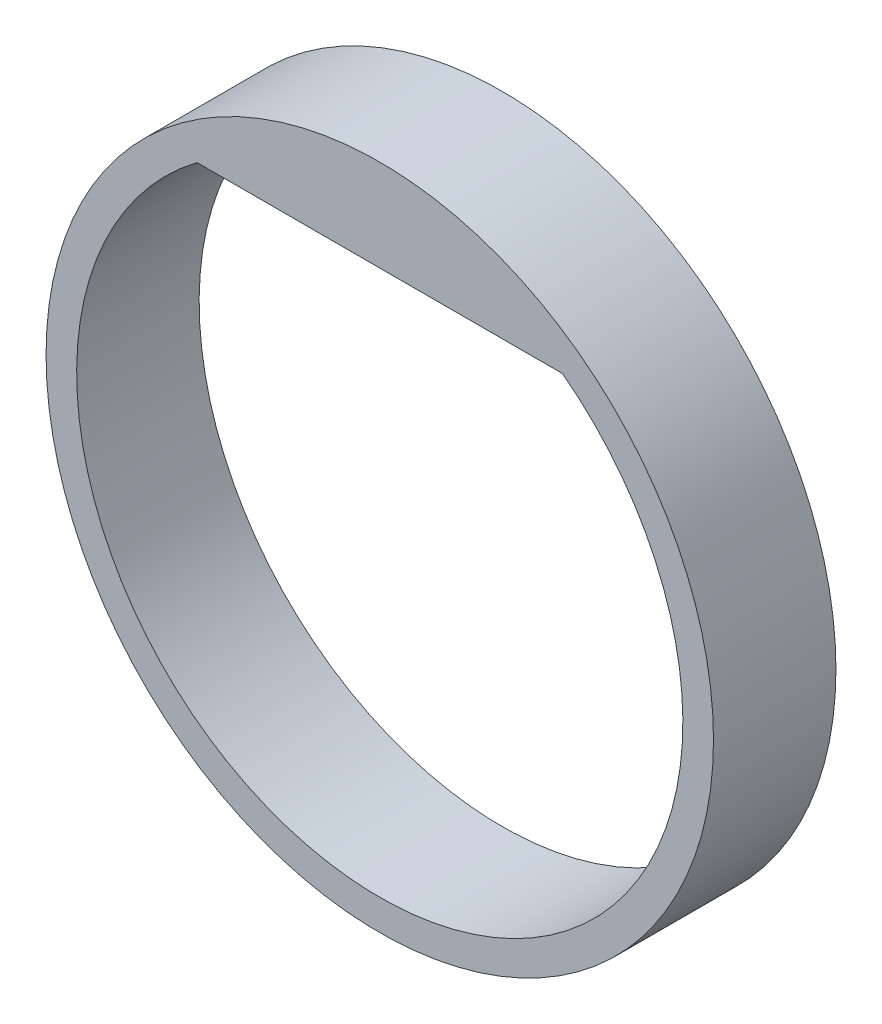
SolidWorks part; units mm, degrees
ref_plane "Vorne" through (0, 0, 0) normal (0, 0, 1) x (1, 0, 0)
ref_plane "Oben" through (0, 0, 0) normal (0, 1, 0) x (1, 0, 0)
ref_plane "Seite" through (0, 0, 0) normal (1, 0, 0) x (0, 0, -1)
sketch "Skizze1" plane through (0, 0, 0) normal (0, 0, 1) x (1, 0, 0)
  line L0 (2.9833, 3.95) -> (-2.9833, 3.95)
  circle A1 centre (0, 0) radius 5.45
  arc A2 (-2.9833, 3.95) -> (2.9833, 3.95) centre (0, 0) ccw
  dimension "D1" = 3.95
  dimension "D2" = 0.5
  dimension "D3" = 4.95
extrude "Aufsatz-Linear austragen1" add sketch "Skizze1" along normal blind 2
